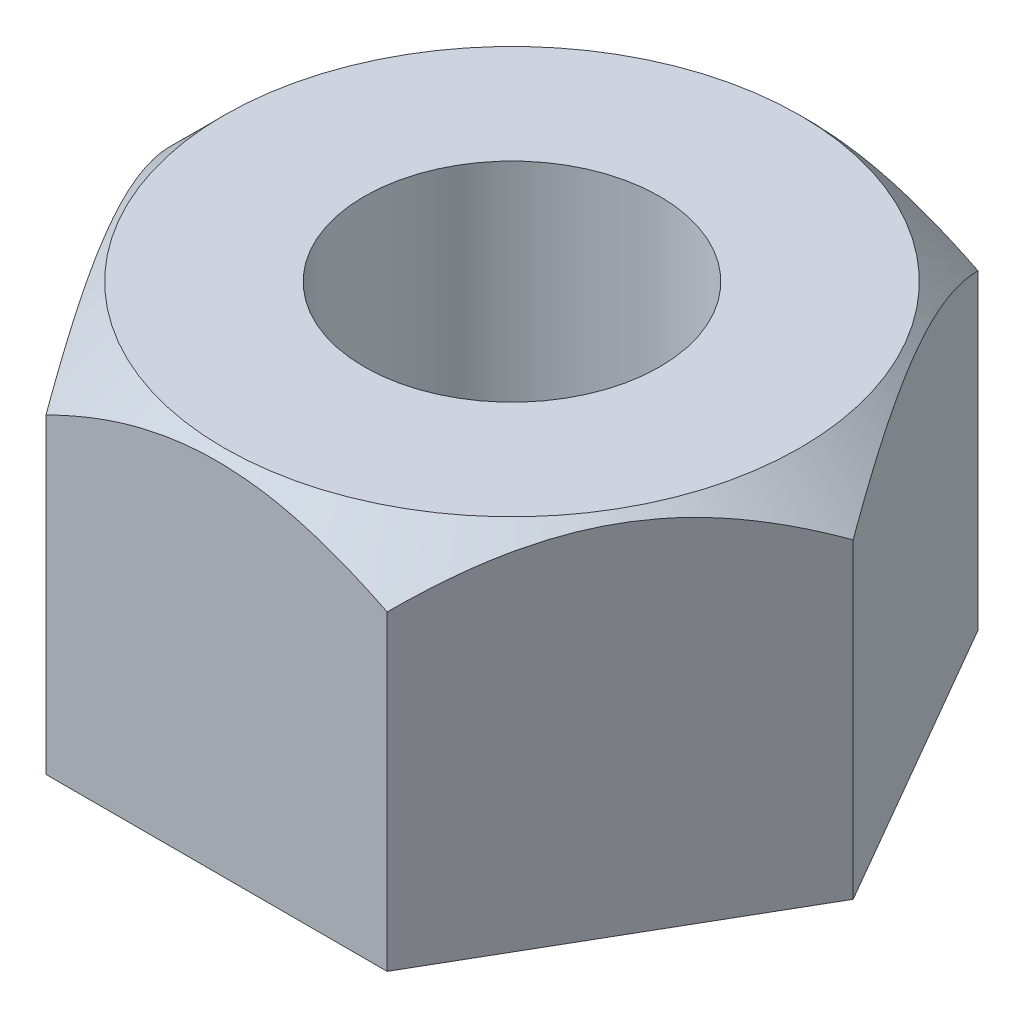
SolidWorks part; units mm, degrees
material "AISI 304"
ref_plane "前视基准面" through (0, 0, 0) normal (0, 0, 1) x (1, 0, 0)
ref_plane "上视基准面" through (0, 0, 0) normal (0, 1, 0) x (1, 0, 0)
ref_plane "右视基准面" through (0, 0, 0) normal (1, 0, 0) x (0, 0, -1)
sketch "草图1" plane through (0, 0, 0) normal (0, 1, 0) x (1, 0, 0)
  line L0 (-6.9282, 12) -> (-13.8564, 0)
  line L1 (-13.8564, 0) -> (-6.9282, -12)
  line L2 (-6.9282, -12) -> (6.9282, -12)
  line L3 (6.9282, -12) -> (13.8564, 0)
  line L4 (13.8564, 0) -> (6.9282, 12)
  line L5 (6.9282, 12) -> (-6.9282, 12)
  circle A0 centre (0, 0) radius 6
  dimension "D1" = 12
  dimension "D2" = 12
  dimension "D3" = 12
  dimension "D4" = 120
  dimension "D5" = 120
  dimension "D6" = 240
  dimension "D7" = 240
  dimension "D8" = 12
  dimension "D9" = 12
  dimension "D10" = 12
  dimension "D11" = 12
extrude "凸台-拉伸1" add sketch "草图1" along normal blind 14.8 contours A0 | L0 L1 L2 L3 L4 L5
sketch "草图2" plane through (0, 0, 0) normal (0, 0, 1) x (1, 0, 0)
  line L0 (0, 17.648) -> (0, -2.6549) construction
  line L1 (9.5, 17) -> (15, 11.5)
  line L2 (15, 11.5) -> (15, 17)
  line L3 (15, 17) -> (9.5, 17)
  line L4 (6.9282, 0) -> (13.8564, 0) construction
  dimension "D1" = 45
  dimension "D2" = 15
  dimension "D3" = 17
  dimension "D4" = 5.5
revolve "切除-旋转1" cut sketch "草图2" angle 360 about L0
